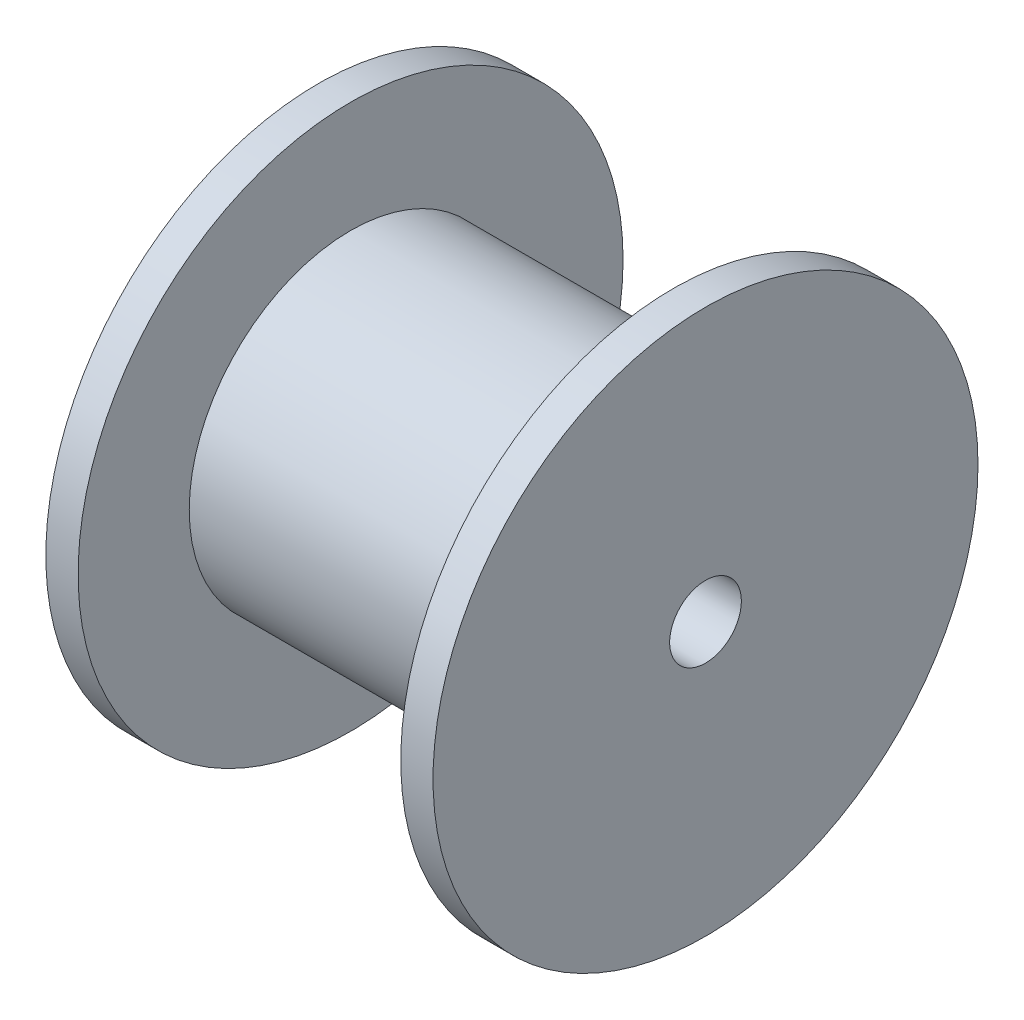
SolidWorks part; units mm, degrees
ref_plane "Alzado" through (0, 0, 0) normal (0, 0, 1) x (1, 0, 0)
ref_plane "Planta" through (0, 0, 0) normal (0, 1, 0) x (1, 0, 0)
ref_plane "Vista lateral" through (0, 0, 0) normal (1, 0, 0) x (0, 0, -1)
sketch "Croquis1" plane through (0, 0, 0) normal (1, 0, 0) x (0, 0, -1)
  circle A0 centre (0, 0) radius 76
  dimension "D1" = 152
extrude "Saliente-Extruir1" add sketch "Croquis1" along normal blind 9
sketch "Croquis2" plane through (9, 0, 0) normal (1, 0, 0) x (0, 0, -1)
  circle A0 centre (0, 0) radius 45
  dimension "D1" = 90
extrude "Saliente-Extruir2" add sketch "Croquis2" along normal blind 90
sketch "Croquis3" plane through (99, 0, 0) normal (1, 0, 0) x (0, 0, -1)
  circle A0 centre (0, 0) radius 76
  dimension "D1" = 152
extrude "Saliente-Extruir3" add sketch "Croquis3" along normal blind 9
sketch "Croquis4" plane through (108, 0, 0) normal (1, 0, 0) x (0, 0, -1)
  circle A0 centre (0, 0) radius 10
  dimension "D1" = 20
extrude "Cortar-Extruir1" cut sketch "Croquis4" against normal blind 108
